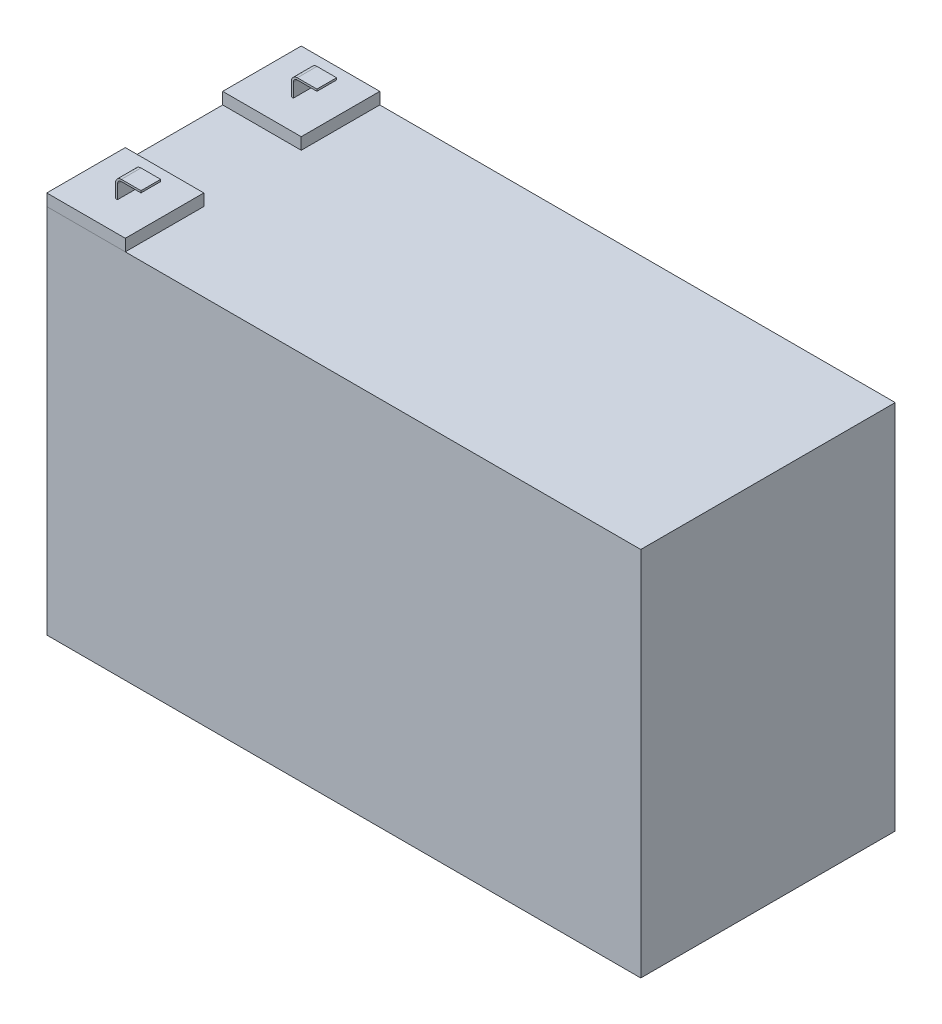
SolidWorks part; units mm, degrees
material "PBT General Purpose"
ref_plane "Front Plane" through (0, 0, 0) normal (0, 0, 1) x (1, 0, 0)
ref_plane "Top Plane" through (0, 0, 0) normal (0, 1, 0) x (1, 0, 0)
ref_plane "Right Plane" through (0, 0, 0) normal (1, 0, 0) x (0, 0, -1)
sketch "Sketch1" plane through (0, 0, 0) normal (0, 1, 0) x (1, 0, 0)
  line L1 (-75.63, -32.4) -> (75.63, -32.4)
  line L2 (-75.63, -32.4) -> (-75.63, 32.4)
  line L3 (-75.63, 32.4) -> (75.63, 32.4)
  line L4 (75.63, -32.4) -> (75.63, 32.4)
  line L5 (0, 32.4) -> (0, -32.4) construction
  line L6 (-75.63, 0) -> (75.63, 0) construction
  point P0 (0, 0)
  dimension "D1" = 64.8
  dimension "D2" = 151.26
extrude "Boss-Extrude1" add sketch "Sketch1" along normal blind 94.5
sketch "Sketch2" plane through (0, 94.5, 0) normal (0, 1, 0) x (1, 0, 0)
  line L1 (-75.63, -32.4) -> (-55.63, -32.4)
  line L2 (-75.63, -32.4) -> (-75.63, -12.4)
  line L3 (-75.63, -12.4) -> (-55.63, -12.4)
  line L4 (-55.63, -32.4) -> (-55.63, -12.4)
  line L5 (-65.63, -12.4) -> (-65.63, -32.4) construction
  line L6 (-75.63, -22.4) -> (-55.63, -22.4) construction
  point P128 (-65.63, -22.4)
  dimension "D1" = 20
  dimension "D2" = 20
extrude "Boss-Extrude2" add sketch "Sketch2" along normal blind 3 separate body
ref_plane "Plane1" through (0, 0, 22.4) normal (0, 0, 1) x (1, 0, 0)
sketch "Sketch3" plane through (0, 0, 22.4) normal (0, 0, 1) x (1, 0, 0)
  line L0 (-65.63, 97.5) -> (-65.63, 101)
  line L1 (-75.63, 97.5) -> (-55.63, 97.5) construction
  line L2 (-64.13, 102.5) -> (-59.13, 102.5)
  line L3 (-65.13, 97.5) -> (-65.13, 101)
  line L4 (-64.13, 102) -> (-59.13, 102)
  line L5 (-65.63, 97.5) -> (-65.13, 97.5)
  line L6 (-59.13, 102.5) -> (-59.13, 102)
  arc A0 (-65.63, 101) -> (-64.13, 102.5) centre (-64.13, 101) cw
  arc A1 (-65.13, 101) -> (-64.13, 102) centre (-64.13, 101) cw
  dimension "D3" = 1.5
  dimension "D2" = 3.5
  dimension "D4" = 5
  dimension "D1" = 0.5
extrude "Boss-Extrude3" add sketch "Sketch3" along normal blind 2.5 and the other way blind 2.5 separate body
mirror "Mirror1" about plane through (0, 0, 0) normal (0, 0, 1) of bodies 103 102
